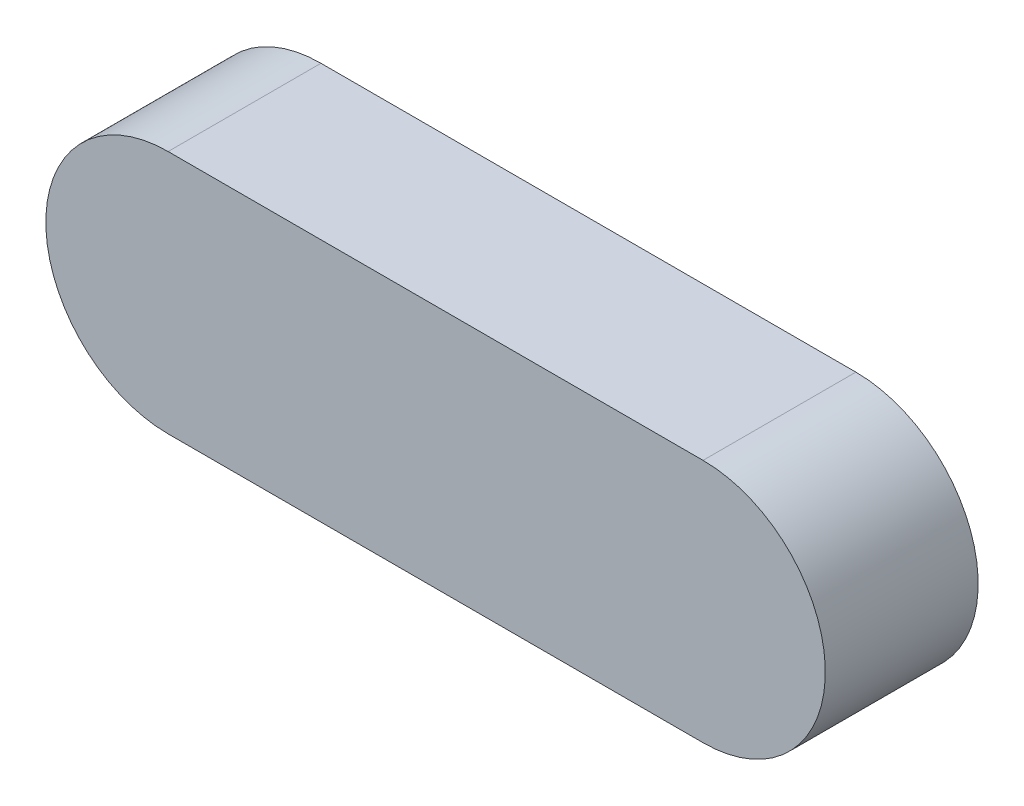
SolidWorks part; units mm, degrees
material "普通碳钢"
ref_plane "前视基准面" through (0, 0, 0) normal (0, 0, 1) x (1, 0, 0)
ref_plane "上视基准面" through (0, 0, 0) normal (0, 1, 0) x (1, 0, 0)
ref_plane "右视基准面" through (0, 0, 0) normal (1, 0, 0) x (0, 0, -1)
sketch "草图1" plane through (0, 0, 0) normal (0, 0, 1) x (1, 0, 0)
  line L0 (0, -27.4898) -> (0, 37.418) construction
  line L1 (-35, 16) -> (35, 16)
  line L3 (-35, -16) -> (35, -16)
  arc A0 (-35, 16) -> (-35, -16) centre (-35, 0) ccw
  arc A1 (35, 16) -> (35, -16) centre (35, 0) cw
  dimension "D1" = 70
  dimension "D3" = 32
  dimension "D4" = 16
extrude "拉伸1" add sketch "草图1" along normal blind 20
